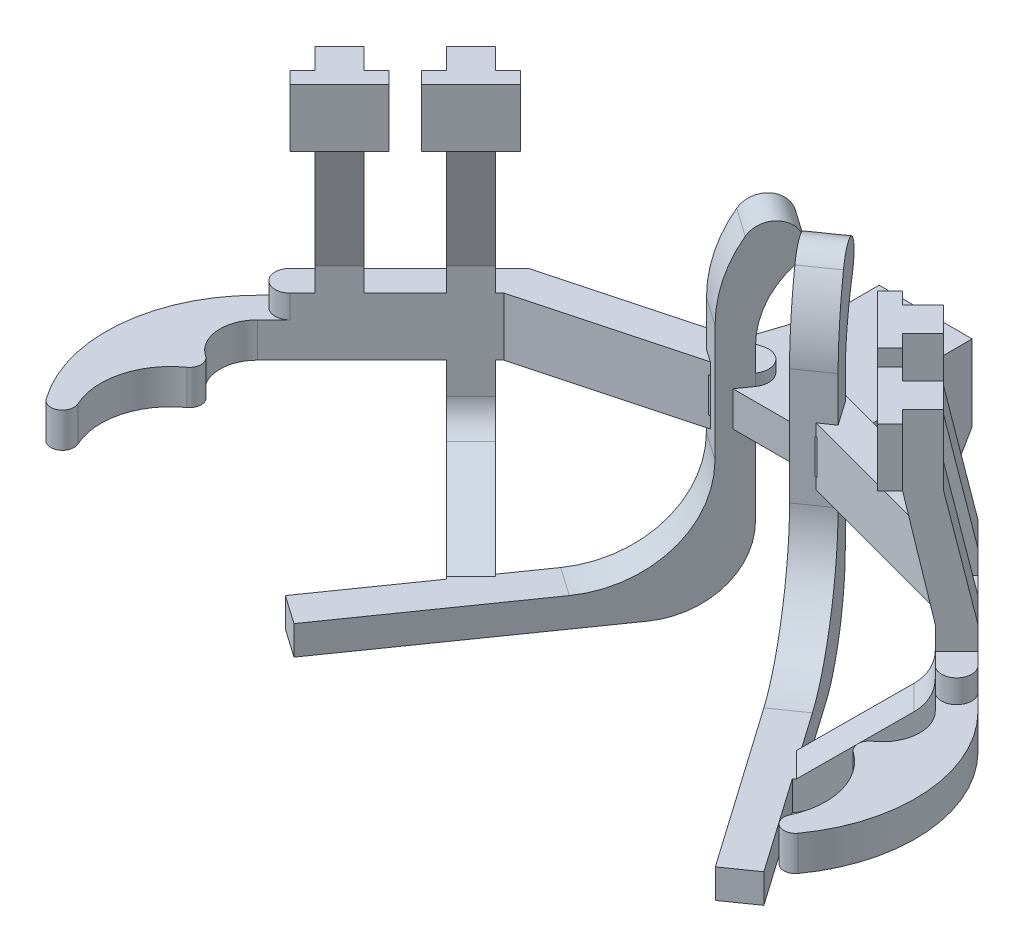
SolidWorks part; units mm, degrees
ref_plane "Front Plane" through (0, 0, 0) normal (0, 0, 1) x (1, 0, 0)
ref_plane "Top Plane" through (0, 0, 0) normal (0, 1, 0) x (1, 0, 0)
ref_plane "Right Plane" through (0, 0, 0) normal (1, 0, 0) x (0, 0, -1)
sketch "Sketch2" plane through (0, 0, 0) normal (0, 1, 0) x (1, 0, 0)
  line L1 (-40, -40) -> (40, -40)
  line L2 (-40, -40) -> (-40, 40)
  line L3 (-40, 40) -> (40, 40)
  line L4 (40, -40) -> (40, 40)
  line L5 (-40, -40) -> (40, 40) construction
  line L6 (-40, 40) -> (40, -40) construction
  point P0 (0, 0)
  dimension "D1" = 80
  dimension "D2" = 80
extrude "Boss-Extrude1" add sketch "Sketch2" along normal blind 100
sketch "Sketch3" plane through (0, 100, 0) normal (0, 1, 0) x (1, 0, 0)
  line L0 (60, -100) -> (60, 0)
  line L1 (60, -100) -> (-60, -100)
  line L2 (60, 0) -> (-60, 0)
  line L3 (-60, -100) -> (-60, 0)
  line L4 (60, -100) -> (-60, 0) construction
  line L5 (60, 0) -> (-60, -100) construction
  point P1 (0, -50)
  dimension "D1" = 120
  dimension "D2" = 50
  dimension "D3" = 100
extrude "Boss-Extrude2" add sketch "Sketch3" against normal blind 30
sketch "Sketch4" plane through (0, 100, 0) normal (0, 1, 0) x (1, 0, 0)
  line L0 (-33.8823, -65.5111) -> (-193.26, -108.2163)
  line L1 (-26.1177, -94.4889) -> (-185.4955, -137.194)
  line L2 (-193.26, -108.2163) -> (-295.7905, -210.7467)
  line L4 (-185.4955, -137.194) -> (-277.4194, -229.1179)
  line L5 (-295.7905, -210.7467) -> (-277.4194, -229.1179) construction
  line L6 (-60, -100) -> (60, -100) construction
  line L7 (0, 0) -> (0, -203.236) construction
  line L8 (295.7905, -210.7467) -> (277.4194, -229.1179) construction
  line L9 (185.4955, -137.194) -> (277.4194, -229.1179)
  line L10 (193.26, -108.2163) -> (295.7905, -210.7467)
  line L11 (26.1177, -94.4889) -> (185.4955, -137.194)
  line L12 (33.8823, -65.5111) -> (193.26, -108.2163)
  line L13 (-30, -80) -> (-119.1812, -207.3639) construction
  line L14 (-199.6376, -151.3362) -> (-218.0088, -132.965) construction
  arc A0 (-26.1177, -94.4889) -> (-33.8823, -65.5111) centre (-30, -80) ccw
  arc A1 (-295.7905, -210.7467) -> (-277.4194, -229.1179) centre (-286.6049, -219.9323) ccw
  arc A2 (295.7905, -210.7467) -> (277.4194, -229.1179) centre (286.6049, -219.9323) cw
  arc A3 (26.1177, -94.4889) -> (33.8823, -65.5111) centre (30, -80) cw
  dimension "D1" = 30
  dimension "D4" = 60
  dimension "D6" = 20
  dimension "D2" = 165
  dimension "D3" = 145
  dimension "D5" = 150
  dimension "D7" = 15
  dimension "D8" = 40
  dimension "D9" = 20
extrude "Boss-Extrude3" add sketch "Sketch4" along normal blind 10 and the other way offset from surface (40 mm away) 10 other way up to face at (0, 70, 35)
ref_plane "Plane1" through (17.4574, 0, 12.2238) normal (-0.8192, 0, -0.5736) x (-0.5736, 0, 0.8192)
sketch "Sketch5" plane through (17.4574, 0, 12.2238) normal (-0.8192, 0, -0.5736) x (-0.5736, 0, 0.8192)
  line L2 (82.7395, 130) -> (82.7395, 0)
  line L4 (107.7395, 148.3868) -> (107.7395, 48.3868)
  line L5 (82.7395, 100) -> (238.2221, 100) construction
  line L6 (197.7395, -41.6132) -> (367.7395, -41.6132)
  line L7 (149.3526, -66.6132) -> (367.7395, -66.6132)
  line L8 (367.7395, -41.6132) -> (367.7395, -66.6132)
  arc A0 (107.7395, 148.3868) -> (89.0659, 212.6748) centre (-12.2605, 148.3868) ccw
  arc A1 (89.0659, 212.6748) -> (58.2904, 187.5681) centre (72.1782, 201.9601) ccw
  arc A2 (58.2904, 187.5681) -> (82.7395, 130) centre (2.7395, 130) cw
  arc A3 (82.7395, 0) -> (149.3526, -66.6132) centre (149.3526, 0) ccw
  arc A4 (107.7395, 48.3868) -> (197.7395, -41.6132) centre (197.7395, 48.3868) ccw
  dimension "D1" = 120
  dimension "D2" = 80
  dimension "D3" = 20
  dimension "D9" = 25
  dimension "D10" = 90
  dimension "D4" = 40
  dimension "D5" = 25
  dimension "D6" = 100
  dimension "D7" = 30
  dimension "D8" = 130
  dimension "D11" = 170
extrude "Boss-Extrude4" add sketch "Sketch5" along normal mid plane 30
ref_plane "Plane2" through (-175.4869, 0, 175.4869) normal (0.7071, 0, -0.7071) x (-0.7071, 0, -0.7071)
sketch "Sketch6" plane through (-175.4869, 0, 175.4869) normal (0.7071, 0, -0.7071) x (-0.7071, 0, -0.7071)
  line L0 (34.1543, 60) -> (34.1543, 33.0477)
  line L1 (21.3616, 8.4731) -> (-50.169, -41.6132)
  line L4 (60.135, 60) -> (60.135, 33.0477)
  line L5 (36.2635, -12.8091) -> (-35.2671, -62.8954)
  line L6 (60.135, 60) -> (34.1543, 60)
  line L7 (-50.169, -41.6132) -> (-50.169, -66.6132)
  line L10 (-35.2671, -62.8954) -> (-50.169, -66.6132)
  arc A0 (34.1543, 33.0477) -> (21.3616, 8.4731) centre (4.1543, 33.0477) cw
  arc A1 (60.135, 33.0477) -> (36.2635, -12.8091) centre (4.1543, 33.0477) cw
  dimension "D2" = 30
  dimension "D1" = 125
extrude "Boss-Extrude5" add sketch "Sketch6" along normal mid plane 30
sketch "Sketch7" plane through (-175.4869, 0, 175.4869) normal (0.7071, 0, -0.7071) x (-0.7071, 0, -0.7071)
  line L0 (60.135, 130) -> (60.135, 110)
  line L1 (60.135, 110) -> (34.1543, 110)
  line L2 (34.1543, 110) -> (34.1543, 130)
  line L3 (34.1543, 130) -> (14.1543, 230)
  line L5 (39.1543, 230) -> (60.135, 130)
  line L6 (39.1543, 230) -> (39.1543, 290)
  line L7 (39.1543, 290) -> (14.1543, 290)
  line L8 (14.1543, 290) -> (14.1543, 230)
  dimension "D1" = 20
  dimension "D2" = 20
  dimension "D3" = 25
  dimension "D4" = 60
  dimension "D5" = 180
extrude "Boss-Extrude6" add sketch "Sketch7" along normal mid plane 30
sketch "Sketch8" plane through (0, 290, 0) normal (0, 1, 0) x (1, 0, 0)
  line L0 (-196.1021, -197.2981) -> (-206.7087, -186.6915)
  line L1 (-196.1021, -197.2981) -> (-153.6757, -154.8717)
  line L2 (-212.012, -156.6395) -> (-194.3343, -138.9618)
  line L3 (-153.6757, -154.8717) -> (-164.2823, -144.2651)
  line L4 (-196.1021, -197.2981) -> (-149.9588, -183.3373) construction
  line L5 (-167.6365, -201.015) -> (-153.6757, -154.8717) construction
  line L6 (-203.1731, -147.8006) -> (-185.4955, -165.4783) construction
  line L7 (-192.5665, -137.194) -> (-213.7797, -158.4072) construction
  line L8 (-174.8889, -154.8717) -> (-196.1021, -176.0849) construction
  line L9 (-212.012, -156.6395) -> (-194.3343, -174.3171)
  line L10 (-194.3343, -174.3171) -> (-206.7087, -186.6915)
  line L11 (-176.6566, -156.6395) -> (-164.2823, -144.2651)
  line L12 (-194.3343, -138.9618) -> (-176.6566, -156.6395)
  point P1 (-163.5304, -187.4434)
  dimension "D1" = 60
  dimension "D2" = 25
  dimension "D3" = 15
extrude "Boss-Extrude7" add sketch "Sketch8" against normal blind 50
pattern_linear "LPattern1" count 2 spacing 80 along (-0.7071, 0, 0.7071) of "Boss-Extrude7", "Boss-Extrude6"
sketch "Sketch9" plane through (0, 60, 0) normal (0, -1, 0) x (1, 0, 0)
  line L0 (-295.7905, 210.7467) -> (-277.4194, 229.1179)
  line L1 (-295.7905, 210.7467) -> (-309.9327, 224.8889)
  line L2 (-277.4194, 229.1179) -> (-291.5615, 243.26)
  line L3 (-309.9327, 224.8889) -> (-291.5615, 243.26) construction
  arc A0 (-309.9327, 224.8889) -> (-323.3401, 393.0054) centre (-218.0088, 316.8128) cw
  arc A1 (-323.3401, 393.0054) -> (-306.1678, 382.9328) centre (-315.2377, 387.1444) cw
  arc A2 (-306.1678, 382.9328) -> (-286.6201, 308.8368) centre (-251.7488, 357.6629) ccw
  arc A3 (-286.6201, 308.8368) -> (-286.8372, 292.4106) centre (-292.432, 300.6991) cw
  arc A4 (-286.8372, 292.4106) -> (-291.5615, 243.26) centre (-268.9341, 265.8875) ccw
  dimension "D2" = 130
  dimension "D3" = 10
  dimension "D4" = 32
  dimension "D5" = 60
  dimension "D6" = 10
  dimension "D1" = 20
  dimension "D7" = 85
  dimension "D8" = 40
extrude "Boss-Extrude8" add sketch "Sketch9" against normal blind 30
sketch "Sketch12" plane through (35.4749, 0, 35.4749) normal (0.7071, 0, 0.7071) x (0.7071, 0, -0.7071)
  line L4 (-263.1759, -66.6132) -> (-248.1759, -66.6132)
  line L5 (-248.1759, -66.6132) -> (-248.1759, -41.6132)
  line L6 (-248.1759, -41.6132) -> (-263.1759, -41.6132)
  line L7 (-263.1759, -41.6132) -> (-263.1759, -66.6132)
  line L8 (-263.1759, -66.6132) -> (-248.1759, -66.6132)
  line L9 (-248.1759, -66.6132) -> (-248.1759, -41.6132)
  line L10 (-248.1759, -41.6132) -> (-263.1759, -41.6132)
  line L11 (-263.1759, -41.6132) -> (-263.1759, -66.6132)
  dimension "D1" = 0
extrude "Boss-Extrude9" add sketch "Sketch12" along normal blind 10
mirror "Mirror1" about plane through (0, 0, 0) normal (1, 0, 0) of "Boss-Extrude9", "Boss-Extrude5", "Boss-Extrude6", "Boss-Extrude7", "LPattern1", "Boss-Extrude8", "Boss-Extrude4"
sketch "Sketch10" plane through (40, 0, 0) normal (1, 0, 0) x (0, 0, -1)
  line L0 (-40, 34.641) -> (-20, 0)
  line L1 (-40, 70) -> (-40, 0) construction
  line L2 (-40, 0) -> (40, 0) construction
  line L3 (-20, 0) -> (-40, 0)
  line L4 (-40, 0) -> (-40, 34.641)
  line L5 (0, 0) -> (0, 83.5031) construction
  line L6 (40, 0) -> (40, 34.641)
  line L7 (20, 0) -> (40, 0)
  line L8 (40, 34.641) -> (20, 0)
  dimension "D1" = 60
  dimension "D2" = 40
extrude "Cut-Extrude1" cut sketch "Sketch10" against normal up to next
sketch "Sketch11" plane through (0, 100, 0) normal (0, 1, 0) x (1, 0, 0)
  line L0 (-40, 0) -> (-60, -60)
  line L1 (40, 0) -> (60, -60)
  line L14 (-25.6925, -100) -> (25.6925, -100)
  line L15 (25.6925, -100) -> (17.7127, -88.6036)
  line L17 (33.8823, -65.5111) -> (60, -72.5093)
  line L18 (60, -72.5093) -> (60, 0)
  line L19 (60, 0) -> (40, 0)
  line L20 (40, 0) -> (40, 40)
  line L21 (40, 40) -> (-40, 40)
  line L22 (-40, 40) -> (-40, 0)
  line L23 (-40, 0) -> (-60, 0)
  line L24 (-60, 0) -> (-60, -72.5093)
  line L25 (-60, -72.5093) -> (-33.8823, -65.5111)
  line L27 (-17.7127, -88.6036) -> (-25.6925, -100)
  line L32 (60, -60) -> (60, 0)
  line L33 (60, 0) -> (40, 0)
  line L37 (-40, 0) -> (-60, 0)
  line L38 (-60, 0) -> (-60, -60)
  arc A2 (33.8823, -65.5111) -> (17.7127, -88.6036) centre (30, -80) ccw
  arc A3 (-17.7127, -88.6036) -> (-33.8823, -65.5111) centre (-30, -80) ccw
  dimension "D2" = 60
  dimension "D3" = 60
  dimension "D1" = 0
extrude "Cut-Extrude2" cut sketch "Sketch11" against normal up to next
